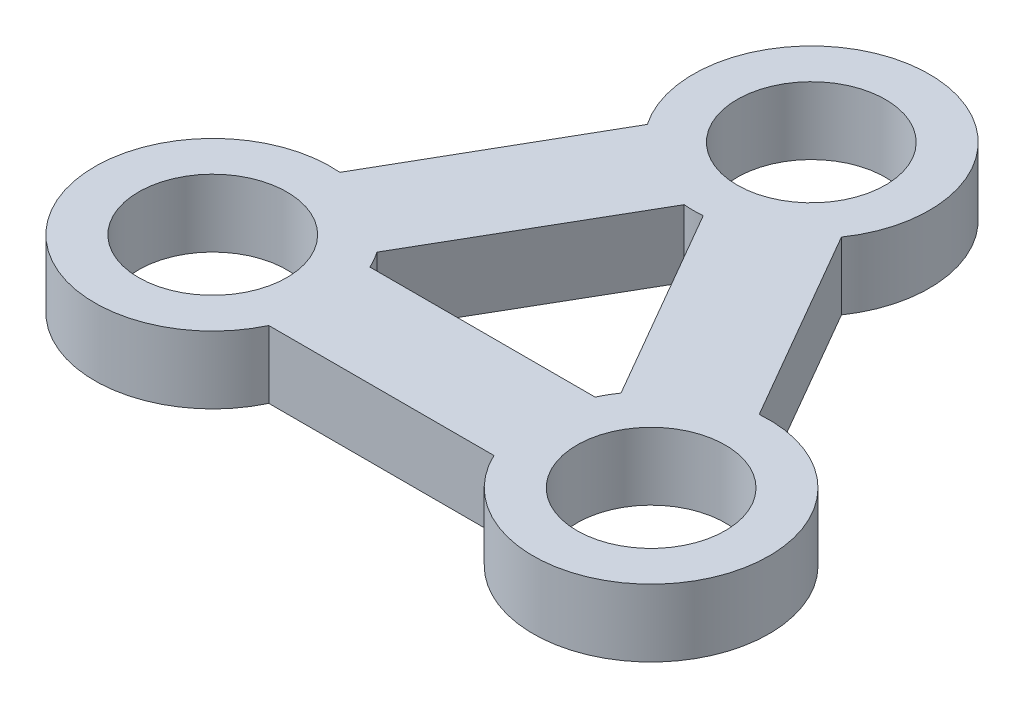
SolidWorks part; units mm, degrees
ref_plane "Front Plane" through (0, 0, 0) normal (0, 0, 1) x (1, 0, 0)
ref_plane "Top Plane" through (0, 0, 0) normal (0, 1, 0) x (1, 0, 0)
ref_plane "Right Plane" through (0, 0, 0) normal (1, 0, 0) x (0, 0, -1)
sketch "Sketch1" plane through (0, 0, 0) normal (0, 1, 0) x (1, 0, 0)
  line L0 (0, 0) -> (11.0061, 19.049) construction
  line L1 (65, 112.5) -> (76.0061, 93.451) construction
  line L2 (130, 0) -> (108, 0) construction
  line L3 (98.3772, 15) -> (31.6228, 15)
  line L4 (28.8081, 19.8769) -> (62.1678, 77.6148)
  line L5 (67.8322, 77.6148) -> (101.1919, 19.8769)
  line L6 (98.3772, -15) -> (31.6228, -15)
  line L8 (93.8081, 92.6231) -> (127.1678, 34.8852)
  line L9 (2.8322, 34.8852) -> (36.0973, 92.7609)
  line L10 (-25.9904, -15) -> (65, 142.4834) construction
  line L11 (155.9904, -15) -> (-25.9904, -15) construction
  line L12 (104.0096, 15) -> (25.9904, 15) construction
  line L13 (25.9904, 15) -> (65, 82.5166) construction
  line L14 (65, 82.5166) -> (104.0096, 15) construction
  line L15 (65, 142.4834) -> (155.9904, -15) construction
  line L16 (53.9939, 93.451) -> (65, 112.5) construction
  line L17 (0, 0) -> (65, 112.5) construction
  line L18 (95, 0) -> (0, 0) construction
  line L19 (130, 0) -> (0, 0) construction
  line L20 (112.4903, 30.3053) -> (130, 0) construction
  line L21 (65, 112.5) -> (130, 0) construction
  circle A0 centre (0, 0) radius 22
  arc A1 (2.8322, 34.8852) -> (31.6228, -15) centre (0, 0) ccw
  arc A3 (98.3772, -15) -> (127.1678, 34.8852) centre (130, 0) ccw
  arc A4 (93.8081, 92.6231) -> (36.0973, 92.7609) centre (65, 112.5) ccw
  circle A5 centre (65, 112.5) radius 22
  circle A6 centre (130, 0) radius 22
  arc A7 (31.6228, 15) -> (28.8081, 19.8769) centre (0, 0) ccw
  arc A8 (101.1919, 19.8769) -> (98.3772, 15) centre (130, 0) ccw
  arc A9 (62.1678, 77.6148) -> (67.8322, 77.6148) centre (65, 112.5) ccw
  point P25 (0, 0)
  point P35 (0, 0)
  dimension "D1" = 130
  dimension "D3" = 65
  dimension "D4" = 70
  dimension "D5" = 44
  dimension "D8" = 35
  dimension "D2" = 112.5
  dimension "D6" = 15
  dimension "D9" = 30
  dimension "D7" = 15
extrude "Boss-Extrude1" add sketch "Sketch1" along normal blind 20
